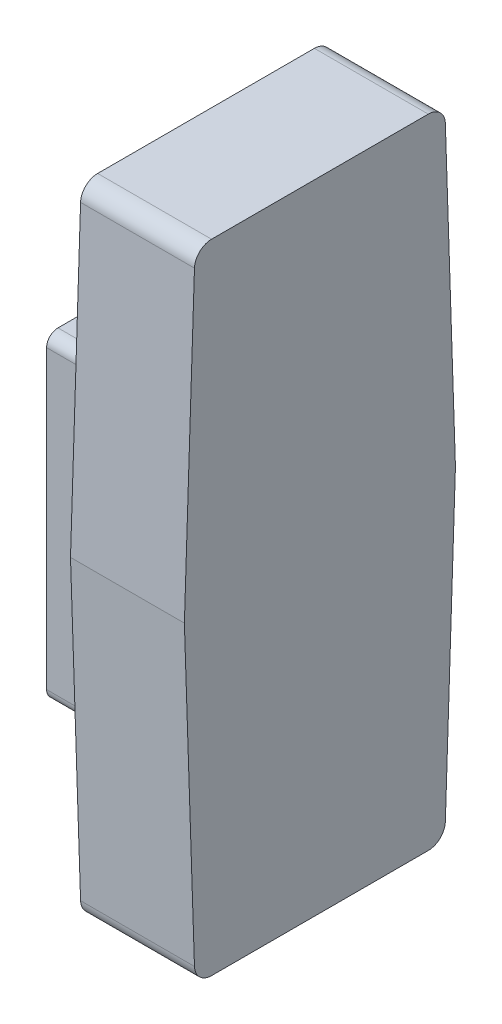
SolidWorks part; units mm, degrees
material "UHMW"
ref_plane "Front Plane" through (0, 0, 0) normal (0, 0, 1) x (1, 0, 0)
ref_plane "Top Plane" through (0, 0, 0) normal (0, 1, 0) x (1, 0, 0)
ref_plane "Right Plane" through (0, 0, 0) normal (1, 0, 0) x (0, 0, -1)
sketch "Sketch1" plane through (0, 0, 0) normal (1, 0, 0) x (0, 0, -1)
  line L6 (0.3808, -13.4747) -> (0.6056, -6.731)
  line L7 (0.6056, -6.731) -> (0.3808, 0.0127)
  line L8 (0, 0.381) -> (-4.8335, 0.381)
  line L9 (-5.2143, 0.0127) -> (-5.4391, -6.731)
  line L10 (-5.4391, -6.731) -> (-5.2143, -13.4747)
  line L11 (-4.8335, -13.843) -> (0, -13.843)
  arc A4 (0.3808, 0.0127) -> (0, 0.381) centre (0, 0) ccw
  arc A5 (-4.8335, 0.381) -> (-5.2143, 0.0127) centre (-4.8335, 0) ccw
  arc A6 (-5.2143, -13.4747) -> (-4.8335, -13.843) centre (-4.8335, -13.462) ccw
  arc A7 (0, -13.843) -> (0.3808, -13.4747) centre (0, -13.462) ccw
extrude "Boss-Extrude1" add sketch "Sketch1" along normal blind 2.54
sketch "Sketch2" plane through (0, 0, 0) normal (-1, 0, 0) x (0, 0, 1)
  line L0 (2.4168, 0.381) -> (2.4168, -13.843) construction
  line L1 (0, 0.381) -> (4.8335, 0.381) construction
  line L2 (4.8335, -13.843) -> (0, -13.843) construction
  line L3 (-0.6056, -6.731) -> (5.4391, -6.731) construction
hole_wizard "CSK for #0 Flat Head Machine Screw (100)1" positions "Sketch4" profile "Sketch3" countersink size "#0" standard "ANSI Inch"
sketch "Sketch4" plane through (0, 0, 0) normal (-1, 0, 0) x (0, 0, 1)
  line L0 (2.4168, -1.5807) -> (2.4168, -5.0142) construction
  line L1 (2.4168, -5.0142) -> (2.4168, -8.4478) construction
  line L4 (2.4168, -8.4478) -> (2.4168, -11.8813) construction
  line L6 (-0.6056, -6.731) -> (5.4391, -6.731) construction
  line L7 (2.4168, 0.381) -> (2.4168, -13.843) construction
  line L8 (2.4168, -11.8813) -> (2.4168, -13.843) construction
  line L10 (2.4168, 0.381) -> (2.4168, -1.5807) construction
  point P0 (2.4168, -1.5807)
  point P2 (2.4168, -5.0142)
  point P6 (2.4168, -8.4478)
  point P8 (2.4168, -11.8813)
sketch "Sketch3" plane through (0, -1.5807, 2.4168) normal (0, 1, 0) x (0, 0, 1)
  line L0 (0, 0) -> (0, 2.54)
  line L1 (0, 2.54) -> (0.635, 2.54)
  line L2 (0.635, 2.54) -> (0.635, 0.5588)
  line L3 (0.635, 0.5588) -> (1.0795, 0)
  line L5 (1.0795, 0) -> (0, 0)
  line L6 (-0.635, 0.5588) -> (-1.0795, 0) construction
  line L11 (0, -6.35) -> (0, 107.95) construction
  dimension "Thru Hole Dia." = 1.27
  dimension "Thru Hole Depth" = 2.54
  dimension "Near C'Sink Dia." = 2.159
  dimension "Near C'Sink Angle" = 77
sketch "Sketch5" plane through (0, 0, 0) normal (-1, 0, 0) x (0, 0, 1)
  line L0 (0.1308, -10.287) -> (4.7028, -10.287)
  line L1 (4.9568, -10.033) -> (4.9568, -3.429)
  line L2 (-0.6056, -6.731) -> (5.4391, -6.731) construction
  line L3 (2.4168, 0.381) -> (2.4168, -13.843) construction
  line L5 (2.4168, -13.843) -> (2.4168, -10.287) construction
  line L6 (2.4168, -10.287) -> (2.4168, -6.731) construction
  line L7 (-0.1232, -10.033) -> (-0.1232, -3.429)
  line L8 (-0.1232, -6.731) -> (4.9568, -6.731) construction
  line L9 (0.1308, -3.175) -> (4.7028, -3.175)
  arc A0 (-0.1232, -10.033) -> (0.1308, -10.287) centre (0.1308, -10.033) ccw
  arc A1 (0.1308, -3.175) -> (-0.1232, -3.429) centre (0.1308, -3.429) ccw
  arc A2 (4.7028, -3.175) -> (4.9568, -3.429) centre (4.7028, -3.429) cw
  arc A3 (4.7028, -10.287) -> (4.9568, -10.033) centre (4.7028, -10.033) ccw
  dimension "D2" = 0.254
  dimension "D3" = 0.254
  dimension "D1" = 2.54
extrude "Boss-Extrude2" add sketch "Sketch5" along normal blind 1.016
sketch "Sketch6" plane through (-1.016, 0, 0) normal (-1, 0, 0) x (0, 0, 1)
  line L0 (2.4168, 0.381) -> (2.4168, -13.843) construction
  line L1 (2.4168, -3.175) -> (2.4168, -5.461) construction
  line L2 (4.7028, -3.175) -> (0.1308, -3.175) construction
  line L3 (2.4168, -5.461) -> (2.4168, -8.001) construction
  line L4 (2.4168, -8.001) -> (2.4168, -10.287) construction
  line L5 (0.1308, -10.287) -> (4.7028, -10.287) construction
  circle A0 centre (2.4168, -5.461) radius 0.635
  circle A1 centre (2.4168, -8.001) radius 0.635
  dimension "D1" = 2.54
  dimension "D2" = 1.27
extrude "Cut-Extrude1" cut sketch "Sketch6" against normal blind 2.54
